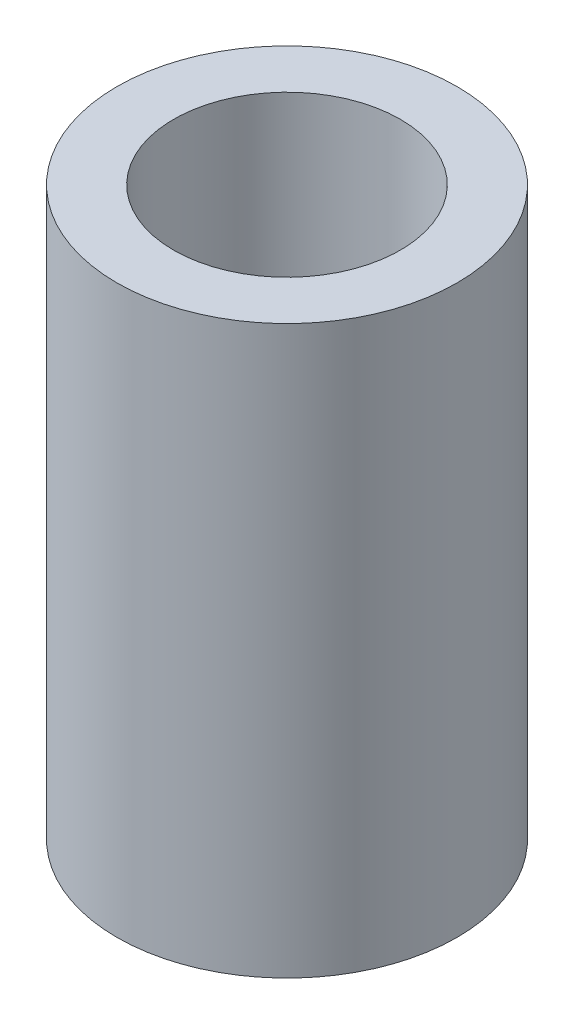
SolidWorks part; units mm, degrees
ref_plane "Front (XY)" through (0, 0, 0) normal (0, 0, 1) x (1, 0, 0)
ref_plane "Top (XZ)" through (0, 0, 0) normal (0, 1, 0) x (1, 0, 0)
ref_plane "Right (YZ)" through (0, 0, 0) normal (1, 0, 0) x (0, 0, -1)
sketch "Sketch1" plane through (0, 0, 0) normal (0, 1, 0) x (1, 0, 0)
  circle A0 centre (0, 0) radius 6
  dimension "D1" = 12
extrude "Boss-Extrude1" add sketch "Sketch1" along normal blind 20
sketch "Sketch2" plane through (0, 20, 0) normal (0, 1, 0) x (1, 0, 0)
  circle A0 centre (0, 0) radius 4
  dimension "D1" = 8
extrude "Cut-Extrude1" cut sketch "Sketch2" against normal through all
